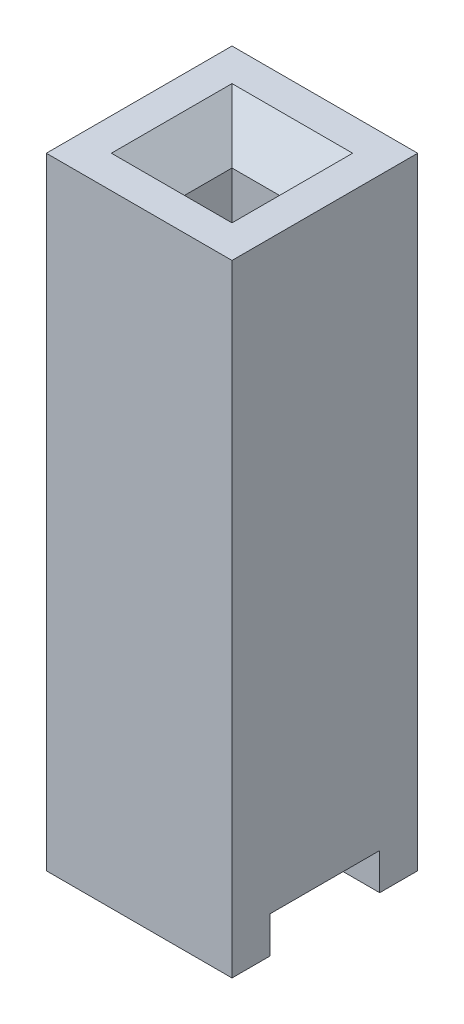
SolidWorks part; units mm, degrees
ref_plane "Спереди" through (0, 0, 0) normal (0, 0, 1) x (1, 0, 0)
ref_plane "Сверху" through (0, 0, 0) normal (0, 1, 0) x (1, 0, 0)
ref_plane "Справа" through (0, 0, 0) normal (1, 0, 0) x (0, 0, -1)
sketch "Эскиз1" plane through (0, 0, 0) normal (0, 1, 0) x (1, 0, 0)
  line L1 (-1.27, 1.27) -> (1.27, 1.27)
  line L2 (-1.27, 1.27) -> (-1.27, -1.27)
  line L3 (-1.27, -1.27) -> (1.27, -1.27)
  line L4 (1.27, 1.27) -> (1.27, -1.27)
  line L5 (-1.27, 1.27) -> (1.27, -1.27) construction
  line L6 (-1.27, -1.27) -> (1.27, 1.27) construction
  point P0 (0, 0)
extrude "Бобышка-Вытянуть1" add sketch "Эскиз1" along normal blind 8.5 contours L1 L4 L3 L2
sketch "Эскиз2" plane through (0, 0, 0) normal (0, 1, 0) x (1, 0, 0)
  line L1 (-1.5, 0.75) -> (1.5, 0.75)
  line L2 (-1.5, 0.75) -> (-1.5, -0.75)
  line L3 (-1.5, -0.75) -> (1.5, -0.75)
  line L4 (1.5, 0.75) -> (1.5, -0.75)
  line L5 (-1.5, 0.75) -> (1.5, -0.75) construction
  line L6 (-1.5, -0.75) -> (1.5, 0.75) construction
  point P0 (0, 0)
extrude "Бобышка-Вытянуть2" add sketch "Эскиз2" along normal blind 0.5 separate body
combine bodies "Соединить2" operation type subtract main body 103 bodies to subtract 104
sketch "Эскиз3" plane through (0, 0.5, 0) normal (0, -1, 0) x (1, 0, 0)
  line L1 (0.3, -0.3) -> (-0.3, -0.3)
  line L2 (0.3, -0.3) -> (0.3, 0.3)
  line L3 (0.3, 0.3) -> (-0.3, 0.3)
  line L4 (-0.3, -0.3) -> (-0.3, 0.3)
  line L5 (0.3, -0.3) -> (-0.3, 0.3) construction
  line L6 (0.3, 0.3) -> (-0.3, -0.3) construction
  point P0 (0, 0)
extrude "Бобышка-Вытянуть3" add sketch "Эскиз3" along normal blind 0.7 separate body
sketch "Эскиз5" plane through (0, 8.5, 0) normal (0, 1, 0) x (1, 0, 0)
  line L1 (-0.325, -0.325) -> (0.325, -0.325)
  line L2 (-0.325, -0.325) -> (-0.325, 0.325)
  line L3 (-0.325, 0.325) -> (0.325, 0.325)
  line L4 (0.325, -0.325) -> (0.325, 0.325)
  line L5 (-0.325, -0.325) -> (0.325, 0.325) construction
  line L6 (-0.325, 0.325) -> (0.325, -0.325) construction
  point P0 (0, 0)
extrude "Бобышка-Вытянуть4" add sketch "Эскиз5" against normal blind 7 separate body
combine bodies "Соединить3" operation type subtract main body 106 bodies to subtract 108
chamfer "Фаска1" distance 0.5 angle 45 4 edges at (0.325, 8.5, 0) (0, 8.5, -0.325) (-0.325, 8.5, 0) (0, 8.5, 0.325)
